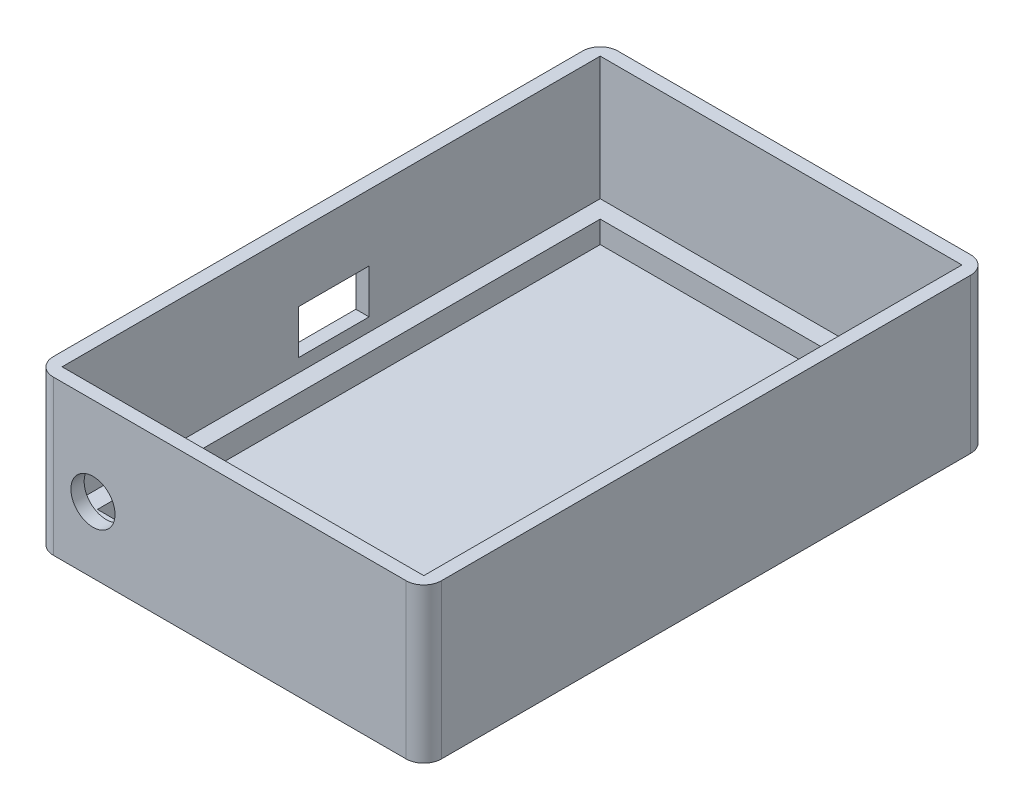
SolidWorks part; units mm, degrees
ref_plane "Front Plane" through (0, 0, 0) normal (0, 0, 1) x (1, 0, 0)
ref_plane "Top Plane" through (0, 0, 0) normal (0, 1, 0) x (1, 0, 0)
ref_plane "Right Plane" through (0, 0, 0) normal (1, 0, 0) x (0, 0, -1)
sketch "Sketch1" plane through (0, 0, 0) normal (0, 1, 0) x (1, 0, 0)
  line L0 (-18.5, -28.5) -> (-18.5, 28.5)
  line L1 (-20, -30) -> (20, -30)
  line L2 (-20, -30) -> (-20, 30)
  line L3 (-20, 30) -> (20, 30)
  line L4 (20, -30) -> (20, 30)
  line L5 (-20, -30) -> (20, 30) construction
  line L6 (-20, 30) -> (20, -30) construction
  line L7 (-18.5, 28.5) -> (18.5, 28.5)
  line L8 (18.5, -28.5) -> (18.5, 28.5)
  line L9 (-18.5, -28.5) -> (18.5, -28.5)
  line L10 (-22, -32) -> (-22, 32)
  line L11 (-22, 32) -> (22, 32)
  line L12 (22, -32) -> (22, 32)
  line L13 (-22, -32) -> (22, -32)
  point P0 (0, 0)
  dimension "D1" = 40
  dimension "D2" = 60
  dimension "D3" = 1.5
  dimension "D4" = 2
extrude "Boss-Extrude1" add sketch "Sketch1" against normal blind 2.5 contours L1 L4 L3 L2 L9 L0 L7 L8 | L10 L13 L12 L11 L4 L1 L2 L3
sketch "Sketch2" plane through (0, 0, 0) normal (0, 1, 0) x (1, 0, 0)
  line L0 (22, -32) -> (22, 32) construction
  line L1 (20.5, 30.5) -> (-20.5, 30.5)
  line L2 (20.5, 30.5) -> (20.5, -30.5)
  line L3 (20.5, -30.5) -> (-20.5, -30.5)
  line L4 (-20.5, 30.5) -> (-20.5, -30.5)
  line L5 (20.5, 30.5) -> (-20.5, -30.5) construction
  line L6 (20.5, -30.5) -> (-20.5, 30.5) construction
  line L7 (-22, -32) -> (22, -32) construction
  line L8 (-22, -32) -> (-22, 32) construction
  line L9 (-22, 32) -> (22, 32) construction
  line L10 (22, -32) -> (22, 32)
  line L11 (-22, -32) -> (22, -32)
  line L12 (-22, -32) -> (-22, 32)
  line L13 (-22, 32) -> (22, 32)
  point P0 (0, 0)
  dimension "D1" = 61
  dimension "D2" = 41
extrude "Boss-Extrude2" add sketch "Sketch2" along normal blind 14
sketch "Sketch3" plane through (0, -2.5, 0) normal (0, -1, 0) x (1, 0, 0)
  line L4 (-22, 32) -> (-22, -32)
  line L5 (-22, -32) -> (22, -32)
  line L6 (22, -32) -> (22, 32)
  line L7 (22, 32) -> (-22, 32)
  line L8 (-22, 32) -> (-22, -32)
  line L9 (-22, -32) -> (22, -32)
  line L10 (22, -32) -> (22, 32)
  line L11 (22, 32) -> (-22, 32)
  dimension "D1" = 0
extrude "Boss-Extrude3" add sketch "Sketch3" along normal blind 1
sketch "Sketch4" plane through (-20.5, 0, 0) normal (1, 0, 0) x (0, 0, -1)
  line L0 (30.5, 0) -> (-30.5, 0) construction
  line L1 (-3.7019, 1.5) -> (4.2981, 1.5)
  line L2 (-3.7019, 1.5) -> (-3.7019, 6.5)
  line L3 (-3.7019, 6.5) -> (4.2981, 6.5)
  line L4 (4.2981, 1.5) -> (4.2981, 6.5)
  line L5 (-3.7019, 1.5) -> (4.2981, 6.5) construction
  line L6 (-3.7019, 6.5) -> (4.2981, 1.5) construction
  point P0 (0.2981, 4)
  dimension "D1" = 5
  dimension "D2" = 8
  dimension "D3" = 1.5
extrude "Cut-Extrude1" cut sketch "Sketch4" against normal blind 8
sketch "Sketch5" plane through (0, 0, 30.5) normal (0, 0, -1) x (-1, 0, 0)
  line L0 (20.5, 0) -> (-20.5, 0) construction
  line L1 (20.5, 14) -> (20.5, 0) construction
  circle A0 centre (15.5, 4) radius 2.5
  dimension "D1" = 4
  dimension "D2" = 5
  dimension "D3" = 5
extrude "Cut-Extrude2" cut sketch "Sketch5" against normal blind 8
fillet "Fillet1" radius 2 4 edges at (-22, 5.25, 32) (22, 5.25, 32) (22, 5.25, -32) (-22, 5.25, -32)
